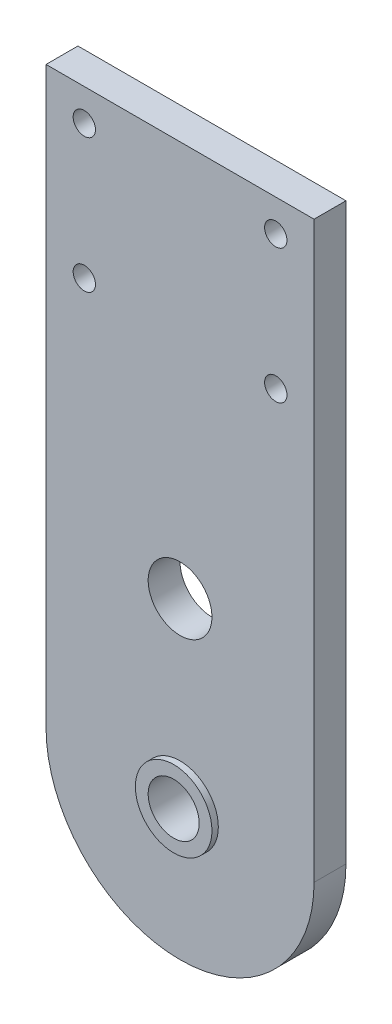
SolidWorks part; units mm, degrees
ref_plane "Front Plane" through (0, 0, 0) normal (0, 0, 1) x (1, 0, 0)
ref_plane "Top Plane" through (0, 0, 0) normal (0, 1, 0) x (1, 0, 0)
ref_plane "Right Plane" through (0, 0, 0) normal (1, 0, 0) x (0, 0, -1)
sketch "Sketch1" plane through (0, 0, 0) normal (0, 0, 1) x (1, 0, 0)
  line L2 (-21, 0) -> (-21, 90)
  line L3 (-21, 90) -> (21, 90)
  line L4 (21, 0) -> (21, 90)
  arc A0 (-21, 0) -> (21, 0) centre (0, 0) ccw
  dimension "D1" = 42
  dimension "D2" = 90
extrude "Boss-Extrude1" add sketch "Sketch1" along normal blind 5
sketch "Sketch2" plane through (0, 0, 0) normal (0, 0, -1) x (-1, 0, 0)
  line L0 (-21, 0) -> (-21, 90) construction
  line L1 (-21, 90) -> (21, 90) construction
  line L2 (0, 102.605) -> (0, 90.4352) construction
  circle A0 centre (-15, 85) radius 1.75
  circle A1 centre (-15, 64) radius 1.75
  circle A2 centre (15, 64) radius 1.75
  circle A3 centre (15, 85) radius 1.75
  dimension "D2" = 3.5
  dimension "D5" = 3.5
  dimension "D1" = 6
  dimension "D3" = 5
  dimension "D4" = 21
  dimension "D6" = 6
extrude "Cut-Extrude1" cut sketch "Sketch2" against normal through all
sketch "Sketch3" plane through (0, 0, 0) normal (0, 0, -1) x (-1, 0, 0)
  circle A0 centre (0, 0) radius 4
  dimension "D1" = 8
extrude "Cut-Extrude2" cut sketch "Sketch3" against normal through all
sketch "Sketch4" plane through (0, 0, 0) normal (0, 0, -1) x (-1, 0, 0)
  circle A0 centre (0, 28) radius 5
  dimension "D1" = 10
  dimension "D2" = 28
extrude "Cut-Extrude3" cut sketch "Sketch4" against normal through all
sketch "Sketch6" plane through (0, 0, 5) normal (0, 0, 1) x (1, 0, 0)
  circle A0 centre (0, 0) radius 4
  circle A1 centre (0, 0) radius 6
  dimension "D1" = 12
extrude "Boss-Extrude3" add sketch "Sketch6" along normal blind 1
